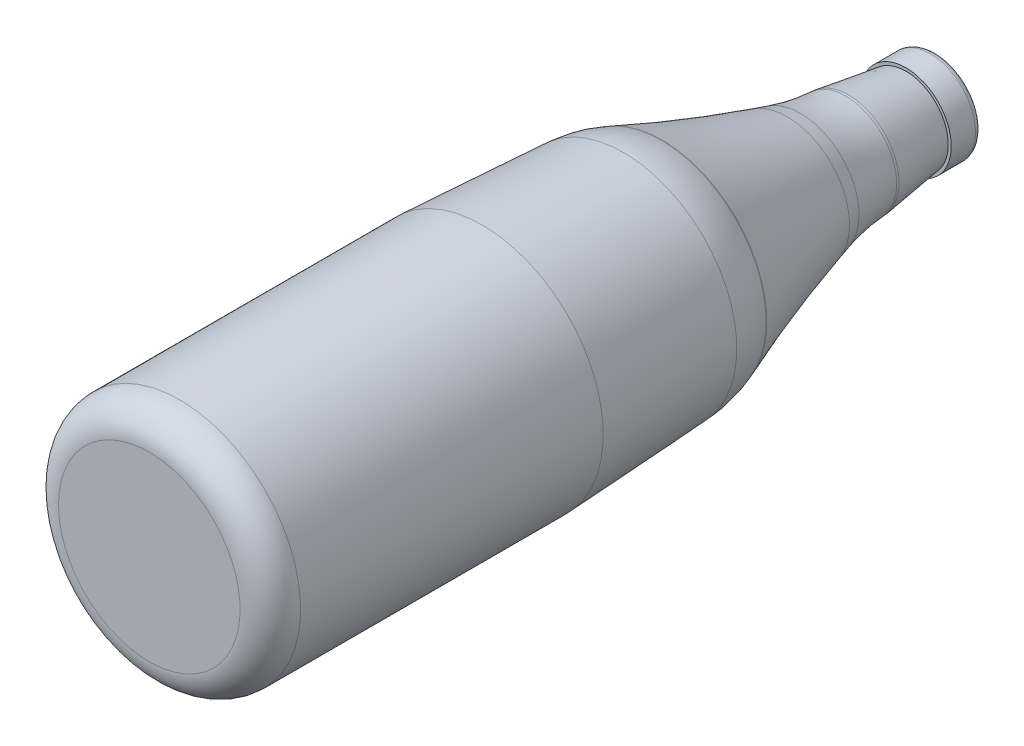
SolidWorks part; units mm, degrees
ref_plane "Front Plane" through (0, 0, 0) normal (0, 0, 1) x (1, 0, 0)
ref_plane "Top Plane" through (0, 0, 0) normal (0, 1, 0) x (1, 0, 0)
ref_plane "Right Plane" through (0, 0, 0) normal (1, 0, 0) x (0, 0, -1)
sketch "Sketch1" plane through (0, 0, 0) normal (0, 1, 0) x (1, 0, 0)
  line L0 (0, 47.7131) -> (0, -186.2739) construction
  line L1 (0, 85.2037) -> (15, 85.2037)
  line L3 (40, -64.7963) -> (40, -164.7963)
  line L4 (0, -174.7963) -> (30, -174.7963)
  line L5 (0, 85.2037) -> (0, -174.7963)
  line L6 (15, 85.2037) -> (15, 75.2037)
  line L7 (16.7554, 56.1873) -> (16.8053, 55.3557)
  line L8 (19.3626, 40.3503) -> (20.6142, 35.9604)
  line L9 (34.588, -5.3451) -> (34.7114, -5.659)
  line L10 (37.4259, -18.0967) -> (40, -64.7963)
  line L11 (15, 75.2037) -> (14, 75.2037)
  line L12 (14, 75.2037) -> (16.7554, 56.1873)
  arc A1 (40, -164.7963) -> (30, -174.7963) centre (30, -164.7963) cw
  arc A4 (19.3626, 40.3503) -> (16.8053, 55.3557) centre (86.6799, 59.5436) cw
  arc A5 (34.588, -5.3451) -> (20.6142, 35.9604) centre (453.3682, 159.3459) cw
  arc A6 (37.4259, -18.0967) -> (34.7114, -5.659) centre (-2.5135, -20.2982) ccw
  dimension "D2" = 14
  dimension "D3" = 10
  dimension "D4" = 10
  dimension "D1" = 15
  dimension "D5" = 100
  dimension "D6" = 40
  dimension "D10" = 140
revolve "Revolve1" add sketch "Sketch1" angle 360 about L0
fillet "Fillet1" radius 2 1 edges at (-15, 0, -85.2037)
